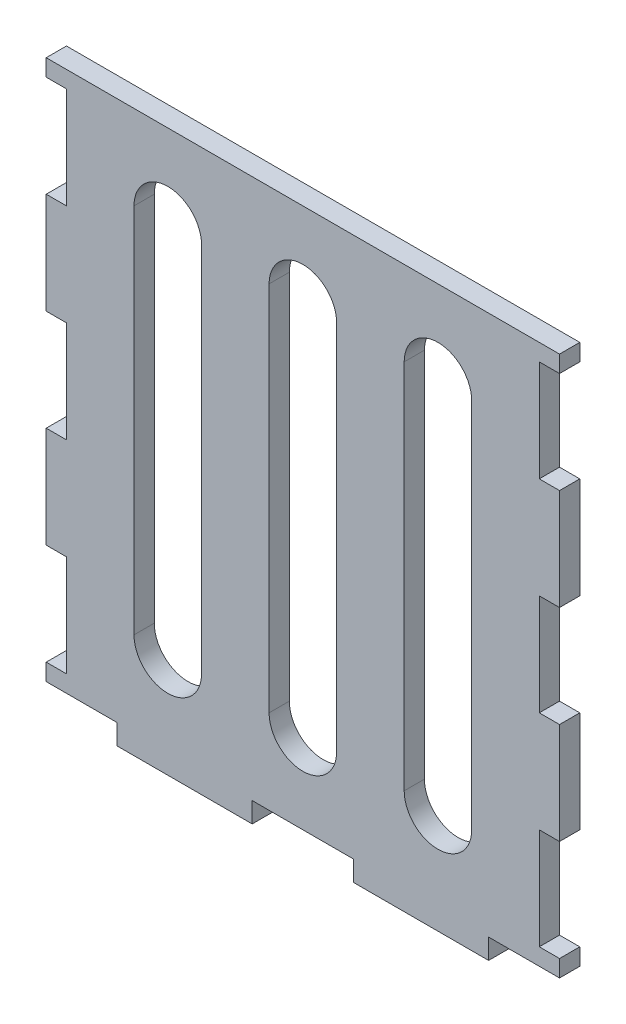
SolidWorks part; units mm, degrees
ref_plane "Front Plane" through (0, 0, 0) normal (0, 0, 1) x (1, 0, 0)
ref_plane "Top Plane" through (0, 0, 0) normal (0, 1, 0) x (1, 0, 0)
ref_plane "Right Plane" through (0, 0, 0) normal (1, 0, 0) x (0, 0, -1)
sketch "Sketch1" plane through (0, 0, 0) normal (0, 0, 1) x (1, 0, 0)
  line L0 (-35, 40) -> (35, 40)
  line L1 (38, -40) -> (-38, -40)
  line L2 (38, -40) -> (38, 40)
  line L3 (38, 40) -> (-38, 40)
  line L4 (-38, -40) -> (-38, 40)
  line L5 (38, -40) -> (-38, 40) construction
  line L6 (38, 40) -> (-38, -40) construction
  line L7 (-38, 40) -> (-35, 40)
  line L8 (35, 22.5) -> (38, 22.5)
  line L9 (35, 22.5) -> (35, 37.5)
  line L10 (35, 37.5) -> (38, 37.5)
  line L11 (38, 22.5) -> (38, 37.5)
  line L12 (35, 22.5) -> (38, 37.5) construction
  line L13 (35, 37.5) -> (38, 22.5) construction
  line L14 (35, -7.5) -> (38, -7.5)
  line L15 (35, -7.5) -> (35, 7.5)
  line L16 (35, 7.5) -> (38, 7.5)
  line L17 (38, -7.5) -> (38, 7.5)
  line L18 (35, -7.5) -> (38, 7.5) construction
  line L19 (35, 7.5) -> (38, -7.5) construction
  line L24 (0, -55) -> (0, 55) construction
  line L25 (-35, 37.5) -> (-38, 37.5)
  line L26 (27.5, -43) -> (7.5, -43)
  line L27 (27.5, -43) -> (27.5, -40)
  line L28 (27.5, -40) -> (7.5, -40)
  line L29 (7.5, -43) -> (7.5, -40)
  line L30 (27.5, -43) -> (7.5, -40) construction
  line L31 (27.5, -40) -> (7.5, -43) construction
  line L32 (-7.5, -43) -> (-27.5, -43)
  line L33 (-7.5, -43) -> (-7.5, -40)
  line L34 (-7.5, -40) -> (-27.5, -40)
  line L35 (-27.5, -43) -> (-27.5, -40)
  line L36 (-7.5, -43) -> (-27.5, -40) construction
  line L37 (-7.5, -40) -> (-27.5, -43) construction
  line L38 (35, -37.5) -> (38, -37.5)
  line L39 (35, -37.5) -> (35, -22.5)
  line L40 (35, -22.5) -> (38, -22.5)
  line L41 (38, -37.5) -> (38, -22.5)
  line L42 (35, -37.5) -> (38, -22.5) construction
  line L43 (35, -22.5) -> (38, -37.5) construction
  line L48 (-38, 22.5) -> (-38, 37.5)
  line L49 (-35, 22.5) -> (-38, 22.5)
  line L50 (0, -27.5) -> (0, 27.5) construction
  line L53 (-5, -27.5) -> (-5, 27.5)
  line L56 (5, -27.5) -> (5, 27.5)
  line L59 (-35, 22.5) -> (-35, 37.5)
  line L60 (-35, 7.5) -> (-38, 7.5)
  line L61 (-38, -7.5) -> (-38, 7.5)
  line L62 (-35, -7.5) -> (-38, -7.5)
  line L63 (-35, -7.5) -> (-35, 7.5)
  line L64 (-35, -22.5) -> (-38, -22.5)
  line L65 (-38, -37.5) -> (-38, -22.5)
  line L66 (-35, -37.5) -> (-38, -37.5)
  line L67 (-35, -37.5) -> (-35, -22.5)
  line L68 (20, -27.5) -> (20, 27.5) construction
  line L69 (15, -27.5) -> (15, 27.5)
  line L70 (25, -27.5) -> (25, 27.5)
  line L71 (-20, -27.5) -> (-20, 27.5) construction
  line L72 (-15, -27.5) -> (-15, 27.5)
  line L73 (-25, -27.5) -> (-25, 27.5)
  arc A6 (-5, -27.5) -> (5, -27.5) centre (0, -27.5) ccw
  arc A7 (5, 27.5) -> (-5, 27.5) centre (0, 27.5) ccw
  arc A8 (15, -27.5) -> (25, -27.5) centre (20, -27.5) ccw
  arc A9 (25, 27.5) -> (15, 27.5) centre (20, 27.5) ccw
  arc A10 (-15, -27.5) -> (-25, -27.5) centre (-20, -27.5) cw
  arc A11 (-25, 27.5) -> (-15, 27.5) centre (-20, 27.5) cw
  point P0 (0, 0)
  point P8 (36.5, 30)
  point P13 (36.5, 0)
  point P23 (17.5, -41.5)
  point P28 (-17.5, -41.5)
  point P34 (36.5, -30)
  point P46 (0, 0)
  point P51 (20, 0)
  point P58 (0, 0)
  point P59 (0, 0)
  point P60 (0, 0)
  point P61 (0, 0)
  point P62 (0, 0)
  point P69 (-20, 0)
  dimension "D9" = 5
  dimension "D1" = 76
  dimension "D2" = 80
  dimension "D3" = 3
  dimension "D4" = 80
  dimension "D5" = 3
  dimension "D6" = 15
  dimension "D7" = 15
  dimension "D8" = 15
  dimension "D10" = 55
  dimension "D11" = 10
  dimension "D12" = 3
  dimension "D13" = 20
  dimension "D14" = 15
  dimension "D15" = 7.5
extrude "Boss-Extrude1" add sketch "Sketch1" along normal blind 3
